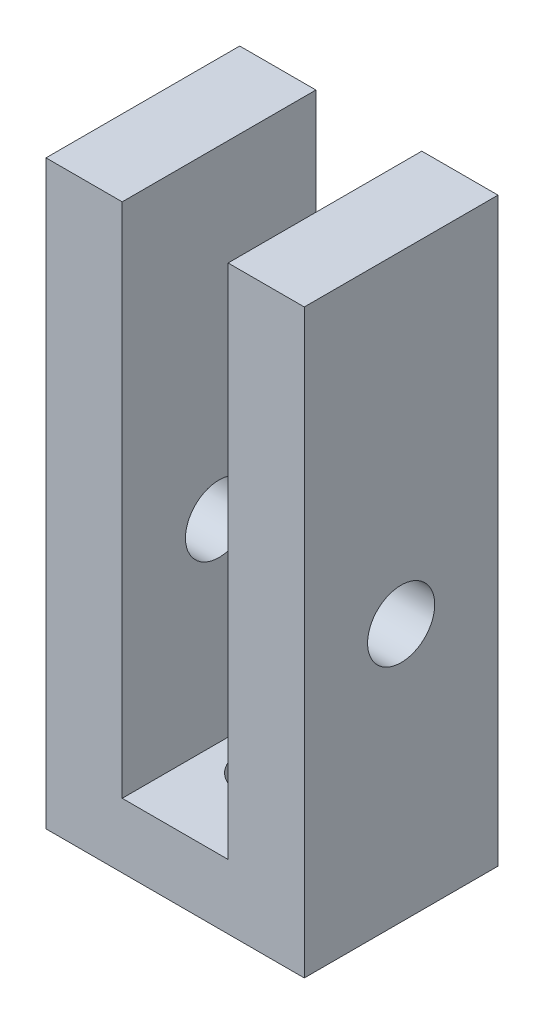
SolidWorks part; units mm, degrees
ref_plane "Спереди" through (0, 0, 0) normal (0, 0, 1) x (1, 0, 0)
ref_plane "Сверху" through (0, 0, 0) normal (0, 1, 0) x (1, 0, 0)
ref_plane "Справа" through (0, 0, 0) normal (1, 0, 0) x (0, 0, -1)
sketch "Эскиз5" plane through (0, 0, 0) normal (0, 1, 0) x (1, 0, 0)
  line L1 (0, 0) -> (20, 0)
  line L2 (0, 0) -> (0, 15)
  line L3 (0, 15) -> (20, 15)
  line L4 (20, 0) -> (20, 15)
  dimension "D1" = 15
  dimension "D2" = 20
extrude "Вытянуть5" add sketch "Эскиз5" along normal blind 5
sketch "Эскиз6" plane through (0, 5, 0) normal (0, 1, 0) x (1, 0, 0)
  line L0 (0, 7.5) -> (20, 7.5) construction
  line L1 (0, 15) -> (0, 0) construction
  line L2 (20, 0) -> (20, 15) construction
  circle A0 centre (10, 7.5) radius 2.6
  dimension "D1" = 5.2
extrude "Вытянуть6" cut sketch "Эскиз6" against normal up to next
sketch "Эскиз7" plane through (0, 5, 0) normal (0, 1, 0) x (1, 0, 0)
  line L0 (0, 0) -> (20, 0) construction
  line L1 (0, 15) -> (5.9, 15)
  line L2 (0, 15) -> (0, 0)
  line L3 (0, 0) -> (5.9, 0)
  line L4 (5.9, 15) -> (5.9, 0)
  line L6 (20, 15) -> (14.1, 15)
  line L7 (20, 15) -> (20, 0)
  line L8 (20, 0) -> (14.1, 0)
  line L9 (14.1, 15) -> (14.1, 0)
  dimension "D1" = 8.2
extrude "Вытянуть7" add sketch "Эскиз7" along normal blind 40
sketch "Эскиз8" plane through (0, 0, 0) normal (-1, 0, 0) x (0, 0, 1)
  line L0 (0, 0) -> (-15, 0) construction
  line L1 (0, 45) -> (0, 0) construction
  circle A0 centre (-7.5, 20) radius 2.6
  dimension "D1" = 5.2
  dimension "D2" = 20
  dimension "D3" = 7.5
extrude "Вытянуть8" cut sketch "Эскиз8" against normal through all
